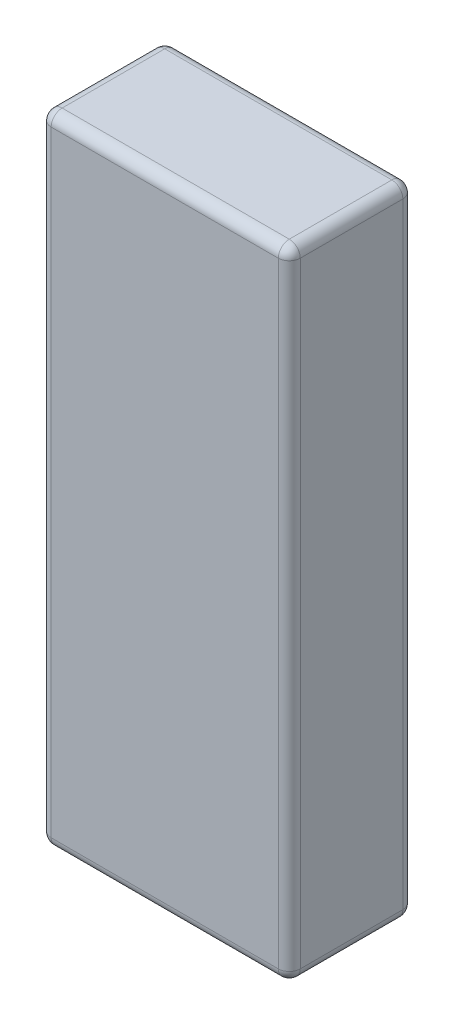
SolidWorks part; units mm, degrees
ref_plane "Front Plane" through (0, 0, 0) normal (0, 0, 1) x (1, 0, 0)
ref_plane "Top Plane" through (0, 0, 0) normal (0, 1, 0) x (1, 0, 0)
ref_plane "Right Plane" through (0, 0, 0) normal (1, 0, 0) x (0, 0, -1)
sketch "Sketch1" plane through (0, 0, 0) normal (0, 0, 1) x (1, 0, 0)
  line L1 (0, 0) -> (34, 0)
  line L2 (0, 0) -> (0, 87)
  line L3 (0, 87) -> (34, 87)
  line L4 (34, 0) -> (34, 87)
  dimension "D1" = 87
  dimension "D2" = 34
extrude "Boss-Extrude1" add sketch "Sketch1" along normal blind 17
fillet "Fillet1" radius 1.5 12 edges at (0, 87, 8.5) (0, 0, 8.5) (34, 0, 8.5) (34, 87, 8.5) (17, 0, 0) (34, 43.5, 0) (17, 87, 0) (0, 43.5, 0) (17, 87, 17) (34, 43.5, 17) (17, 0, 17) (0, 43.5, 17)
